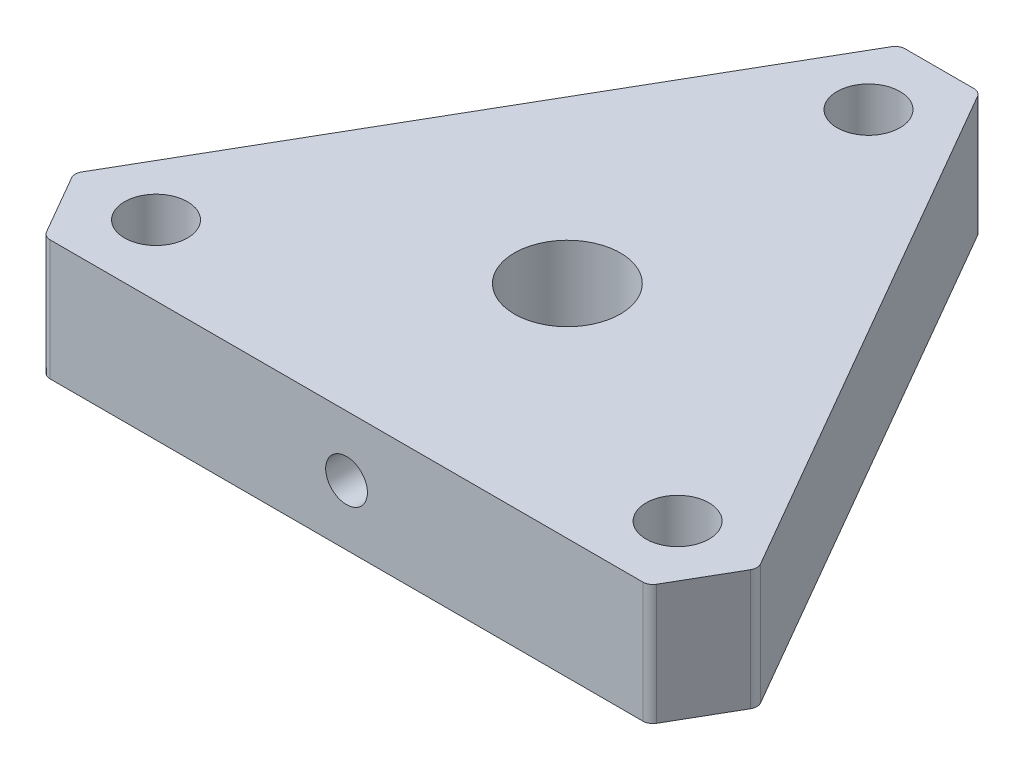
SolidWorks part; units mm, degrees
material "6061 Alloy"
ref_plane "Front Plane" through (0, 0, 0) normal (0, 0, 1) x (1, 0, 0)
ref_plane "Top Plane" through (0, 0, 0) normal (0, 1, 0) x (1, 0, 0)
ref_plane "Right Plane" through (0, 0, 0) normal (1, 0, 0) x (0, 0, -1)
sketch "Sketch1" plane through (0, 0, 0) normal (0, 1, 0) x (1, 0, 0)
  line L0 (0, 0) -> (0, 34.925) construction
  line L1 (0, 0) -> (30.2459, -17.4625) construction
  line L2 (0, 0) -> (-30.2459, -17.4625) construction
  line L3 (0, 34.925) -> (30.2459, -17.4625)
  line L4 (30.2459, -17.4625) -> (-30.2459, -17.4625)
  line L5 (-30.2459, -17.4625) -> (0, 34.925)
  circle A0 centre (0, 0) radius 34.925 construction
  circle A1 centre (0, 0) radius 23.8125 construction
  circle A2 centre (0, 23.8125) radius 2.4892 construction
  circle A3 centre (0, 0) radius 12.7
  circle A4 centre (0, 0) radius 4.191
  circle A5 centre (20.6222, 11.9063) radius 2.4892 construction
  circle A6 centre (20.6222, -11.9062) radius 2.4892 construction
  circle A7 centre (0, -23.8125) radius 2.4892 construction
  circle A8 centre (-20.6222, -11.9063) radius 2.4892 construction
  circle A9 centre (-20.6222, 11.9062) radius 2.4892 construction
  point P20 (0, 0)
  point P35 (0, 0)
  dimension "D1" = 4.9784
  dimension "D2" = 47.625
  dimension "D3" = 69.85
  dimension "D4" = 8.382
  dimension "D5" = 25.4
  dimension "D6" = 6
extrude "Boss-Extrude1" add sketch "Sketch1" against normal blind 9.525
hole_wizard "#10 Clearance Hole1" positions "3DSketch1" profile "Sketch2" hole size "#10" standard "ANSI Inch" end condition through all
sketch3d "3DSketch1"
  point P0 (0, 0, -23.8125)
  point P2 (20.6222, 0, 11.9062)
  point P4 (-20.6222, 0, 11.9063)
sketch "Sketch2" plane through (0, 0, -23.8125) normal (1, 0, 0) x (0, 0, 1)
  line L0 (0, 0) -> (0, 9.525)
  line L1 (0, 9.525) -> (2.4892, 9.525)
  line L2 (2.4892, 9.525) -> (2.4892, 0)
  line L5 (2.4892, 0) -> (0, 0)
  line L11 (0, -6.35) -> (0, 107.95) construction
  dimension "Thru Hole Dia." = 4.9784
  dimension "Thru Hole Depth" = 9.525
sketch "Sketch3" plane through (0, 0, 17.4625) normal (0, 0, 1) x (1, 0, 0)
  line L0 (0, 0) -> (0, -9.525)
  line L1 (30.2459, -9.525) -> (-30.2459, -9.525) construction
  circle A0 centre (0, -4.7625) radius 2
  dimension "D1" = 4
hole_wizard "Tap Drill for M4x0.7 Tap1" positions "3DSketch2" profile "Sketch4" hole size "M4x0.7" standard "ANSI Metric"
sketch3d "3DSketch2"
  point P0 (0, -4.7625, 17.4625)
  point P3 (0, -4.7625, 17.4625)
sketch "Sketch4" plane through (0, -4.7625, 17.4625) normal (1, 0, 0) x (0, -1, 0)
  line L0 (0, 0) -> (0, 13.2715)
  line L1 (0, 13.2715) -> (1.65, 13.2715)
  line L2 (1.65, 13.2715) -> (1.65, 0)
  line L5 (1.65, 0) -> (0, 0)
  line L11 (0, -6.35) -> (0, 107.95) construction
  dimension "Thru Hole Dia." = 3.3
  dimension "Thru Hole Depth" = 13.2715
chamfer "Chamfer1" distance 6.35 angle 60 3 edges at (-30.2459, -4.7625, 17.4625) (30.2459, -4.7625, 17.4625) (0, -4.7625, -34.925)
fillet "Fillet2" radius 0.7937 6 edges at (-3.175, -4.7625, -29.4257) (3.175, -4.7625, -29.4257) (27.0709, -4.7625, 11.9632) (23.8959, -4.7625, 17.4625) (-27.0709, -4.7625, 11.9632) (-23.8959, -4.7625, 17.4625)
